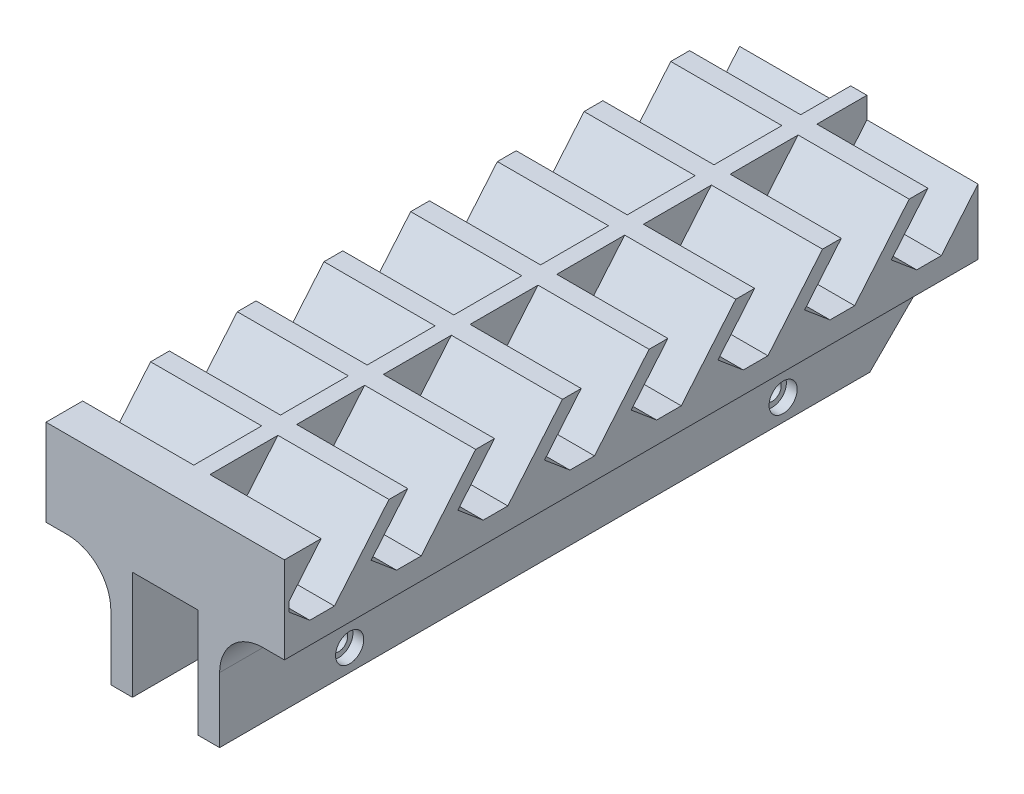
SolidWorks part; units mm, degrees
ref_plane "Front Plane" through (0, 0, 0) normal (0, 0, 1) x (1, 0, 0)
ref_plane "Top Plane" through (0, 0, 0) normal (0, 1, 0) x (1, 0, 0)
ref_plane "Right Plane" through (0, 0, 0) normal (1, 0, 0) x (0, 0, -1)
sketch "Sketch1" plane through (0, 0, 0) normal (0, 0, 1) x (1, 0, 0)
  line L0 (-15.9385, 22.225) -> (15.9385, 22.225)
  line L1 (-9.5885, 15.875) -> (9.5885, 15.875)
  line L2 (-9.5885, 15.875) -> (-9.5885, -15.875)
  line L4 (9.5885, 15.875) -> (9.5885, -15.875)
  line L5 (-9.5885, 15.875) -> (9.5885, -15.875) construction
  line L6 (-9.5885, -15.875) -> (9.5885, 15.875) construction
  line L10 (-15.9385, -22.225) -> (15.9385, -22.225) construction
  line L11 (-9.5885, -15.875) -> (9.5885, -15.875) construction
  line L12 (-15.9385, 22.225) -> (-15.9385, -22.225) construction
  line L13 (-15.9385, 22.225) -> (-15.9385, -15.875)
  line L14 (-15.9385, -15.875) -> (-9.5885, -15.875)
  line L15 (15.9385, 22.225) -> (15.9385, -15.875)
  line L16 (15.9385, 22.225) -> (15.9385, -22.225) construction
  line L17 (15.9385, -15.875) -> (9.5885, -15.875)
  point P0 (0, 0)
  dimension "D2" = 19.177
  dimension "D3" = 31.75
  dimension "D1" = 6.35
extrude "Boss-Extrude1" add sketch "Sketch1" along normal mid plane 203.2
hole_wizard "#10 Clearance Hole1" positions "Sketch2" profile "Sketch3" hole size "#10" standard "ANSI Inch" end condition through all
sketch "Sketch2" plane through (15.9385, 0, 0) normal (1, 0, 0) x (0, 0, -1)
  line L0 (-101.6, -15.875) -> (101.6, -15.875) construction
  line L1 (-63.5, -9.525) -> (63.5, -9.525)
  point P0 (-63.5, -9.525)
  point P9 (63.5, -9.525)
  point P16 (0, -9.525)
  dimension "D1" = 6.35
  dimension "D2" = 127
sketch "Sketch3" plane through (15.9385, -9.525, 63.5) normal (0, 1, 0) x (0, 0, -1)
  line L0 (0, 0) -> (0, 31.877)
  line L1 (0, 31.877) -> (2.6035, 31.877)
  line L2 (2.6035, 31.877) -> (2.6035, 0)
  line L5 (2.6035, 0) -> (0, 0)
  line L11 (0, -6.35) -> (0, 107.95) construction
  dimension "Thru Hole Dia." = 5.207
  dimension "Thru Hole Depth" = 31.877
chamfer "Chamfer1" [suppressed] distance 12.7 angle 45
sketch "Sketch8" plane through (0, 22.225, 0) normal (0, 1, 0) x (1, 0, 0)
  line L0 (15.9385, -101.6) -> (-15.9385, -101.6) construction
  line L1 (-34.925, 101.6) -> (34.925, 101.6)
  line L2 (-34.925, 101.6) -> (-34.925, -101.6)
  line L3 (-34.925, -101.6) -> (34.925, -101.6)
  line L4 (34.925, 101.6) -> (34.925, -101.6)
  line L5 (-34.925, 101.6) -> (34.925, -101.6) construction
  line L6 (-34.925, -101.6) -> (34.925, 101.6) construction
  point P0 (0, 0)
  dimension "D1" = 69.85
extrude "Boss-Extrude4" add sketch "Sketch8" against normal up to surface (6.35 mm away) up to face at (0, 15.875, 0)
sketch "Sketch4" [suppressed] plane through (15.9385, 0, 0) normal (1, 0, 0) x (0, 0, -1)
  line L5 (-63.5, -3.175) -> (-63.5, 15.875) construction
  line L6 (0, 47.625) -> (-63.5, 47.625)
  line L8 (0, 47.625) -> (0, -3.175)
  line L9 (0, -3.175) -> (-63.5, -3.175)
  line L10 (-63.5, 47.625) -> (-63.5, -3.175)
  line L11 (0, 47.625) -> (-63.5, -3.175) construction
  line L12 (0, -3.175) -> (-63.5, 47.625) construction
  line L13 (-63.5, 22.225) -> (63.5, 22.225) construction
  point P0 (-31.75, 22.225)
extrude "Boss-Extrude2" [suppressed] add sketch "Sketch4" against normal blind 4.7625
sketch "Sketch5" [suppressed] plane through (-15.9385, 0, 0) normal (-1, 0, 0) x (0, 0, 1)
  line L0 (-63.5, 15.875) -> (-63.5, -3.175) construction
  line L1 (0, 47.625) -> (-63.5, 47.625)
  line L2 (0, 47.625) -> (0, 22.225)
  line L3 (0, 22.225) -> (-63.5, 22.225)
  line L4 (-63.5, 47.625) -> (-63.5, 22.225)
  line L5 (0, 47.625) -> (-63.5, 22.225) construction
  line L6 (0, 22.225) -> (-63.5, 47.625) construction
  line L7 (0, 47.625) -> (63.5, 47.625) construction
  line L8 (63.5, 22.225) -> (-63.5, 22.225) construction
  point P0 (-31.75, 34.925)
extrude "Boss-Extrude3" [suppressed] add sketch "Sketch5" against normal blind 4.7625
fillet "Fillet1" [suppressed] radius 12.7
hole_wizard "#12 Clearance Hole1" [suppressed] positions "Sketch6" profile "Sketch7" hole size "#12" standard "ANSI Inch"
sketch "Sketch6" [suppressed] plane through (-14.351, 0, 0) normal (-1, 0, 0) x (0, 0, 1)
  arc A0 (-12.7, 44.45) -> (0, 31.75) centre (-12.7, 31.75) ccw construction
  arc A1 (25.4, 31.75) -> (12.7, 44.45) centre (12.7, 31.75) ccw construction
  point P0 (-12.7, 31.75)
  point P2 (12.7, 31.75)
sketch "Sketch7" plane through (-14.351, 31.75, -12.7) normal (0, 1, 0) x (0, 0, 1)
  line L0 (0, 0) -> (0, 46.101)
  line L1 (0, 46.101) -> (2.8956, 46.101)
  line L2 (2.8956, 46.101) -> (2.8956, 0)
  line L5 (2.8956, 0) -> (0, 0)
  line L11 (0, -6.35) -> (0, 107.95) construction
  dimension "Thru Hole Dia." = 5.7912
  dimension "Thru Hole Depth" = 46.101
sketch "Sketch9" plane through (0, 0, 0) normal (1, 0, 0) x (0, 0, -1)
  line L0 (-101.6, 15.875) -> (-101.6, 22.225) construction
  line L1 (-101.6, 41.275) -> (101.6, 41.275)
  line L2 (-101.6, 41.275) -> (-101.6, 22.225)
  line L3 (-101.6, 22.225) -> (101.6, 22.225)
  line L4 (101.6, 41.275) -> (101.6, 22.225)
  line L5 (-101.6, 41.275) -> (101.6, 22.225) construction
  line L6 (-101.6, 22.225) -> (101.6, 41.275) construction
  point P0 (0, 31.75)
  dimension "D1" = 19.05
extrude "Boss-Extrude5" add sketch "Sketch9" against normal mid plane 4.7625
fillet "Fillet2" [suppressed] radius 12.7
sketch "Sketch13" plane through (15.9385, 0, 0) normal (1, 0, 0) x (0, 0, -1)
  circle A0 centre (-63.5, -9.525) radius 4.1275
  circle A1 centre (63.5, -9.525) radius 4.1275
  circle A3 centre (63.5, -9.525) radius 2.6035 construction
  dimension "D1" = 8.255
extrude "Cut-Extrude1" cut sketch "Sketch13" against normal blind 3.175
fillet "Fillet3" radius 12.7 2 edges at (15.9385, 15.875, 0) (-15.9385, 15.875, 0)
fillet "Fillet4" [suppressed] radius 12.7
sketch "Sketch14" plane through (2.3813, 0, 0) normal (1, 0, 0) x (0, 0, -1)
  line L0 (-101.6, 31.75) -> (101.6, 31.75) construction
  line L1 (-101.6, 41.275) -> (-101.6, 22.225) construction
  line L2 (101.6, 22.225) -> (101.6, 41.275) construction
  point P6 (-88.9, 31.75)
  point P9 (-63.5, 31.75)
  point P10 (-38.1, 31.75)
  point P11 (-12.7, 31.75)
  point P12 (12.7, 31.75)
  point P13 (38.1, 31.75)
  point P14 (63.5, 31.75)
  point P15 (88.9, 31.75)
  point P17 (0, 0)
  dimension "D2" = 12.7
  dimension "D3" = 12.7
  dimension "D1" = 8
hole_wizard "1/4 (0.25) Diameter Hole1" positions "Sketch14" profile "Sketch15" hole size "1/4" standard "ANSI Inch"
sketch "Sketch15" plane through (2.3813, 31.75, -88.9) normal (0, 1, 0) x (0, 0, -1)
  line L0 (0, 0) -> (0, 13.8457)
  line L1 (0, 13.8457) -> (3.175, 11.938)
  line L2 (3.175, 11.938) -> (3.175, 0)
  line L5 (3.175, 0) -> (0, 0)
  line L10 (0, 13.8457) -> (-3.175, 11.938) construction
  line L11 (0, -6.35) -> (0, 107.95) construction
  dimension "Hole Dia." = 6.35
  dimension "Hole Depth" = 11.938
  dimension "Drill Angle" = 118
sketch "Sketch16" plane through (0, 0, 0) normal (1, 0, 0) x (0, 0, -1)
  line L0 (-86.9452, 22.225) -> (-70.9604, 41.275)
  line L1 (-94.7373, 36.648) -> (-83.0627, 26.852) construction
  line L2 (-101.6, 28.4693) -> (-90.8548, 41.275)
  line L3 (-101.6, 28.4693) -> (-94.1583, 22.225)
  line L4 (101.6, 22.225) -> (101.6, 41.275)
  line L5 (101.6, 41.275) -> (-101.6, 41.275)
  line L6 (-101.6, 41.275) -> (-101.6, 22.225)
  line L7 (-101.6, 22.225) -> (101.6, 22.225)
  line L8 (101.6, 22.225) -> (101.6, 41.275)
  line L9 (101.6, 41.275) -> (-101.6, 41.275)
  line L10 (-101.6, 41.275) -> (-101.6, 22.225)
  line L11 (-101.6, 22.225) -> (101.6, 22.225)
  line L12 (-81.4396, 22.225) -> (-65.4548, 41.275)
  line L13 (-57.6627, 26.852) -> (-69.3373, 36.648) construction
  line L14 (-56.0396, 22.225) -> (-40.0548, 41.275)
  line L15 (-61.5452, 22.225) -> (-45.5604, 41.275)
  line L16 (-30.6396, 22.225) -> (-14.6548, 41.275)
  line L17 (-36.1452, 22.225) -> (-20.1604, 41.275)
  line L18 (-5.2396, 22.225) -> (10.7452, 41.275)
  line L19 (-10.7452, 22.225) -> (5.2396, 41.275)
  line L20 (20.1604, 22.225) -> (36.1452, 41.275)
  line L21 (14.6548, 22.225) -> (30.6396, 41.275)
  line L22 (45.5604, 22.225) -> (61.5452, 41.275)
  line L23 (40.0548, 22.225) -> (56.0396, 41.275)
  line L24 (70.9604, 22.225) -> (86.9452, 41.275)
  line L25 (65.4548, 22.225) -> (81.4396, 41.275)
  line L26 (96.3604, 22.225) -> (101.6, 28.4693)
  line L27 (90.8548, 22.225) -> (101.6, 35.0307)
  line L28 (-76.2, 28.4693) -> (-68.7583, 22.225)
  line L29 (-50.8, 28.4693) -> (-43.3583, 22.225)
  line L30 (-25.4, 28.4693) -> (-17.9583, 22.225)
  line L31 (0, 28.4693) -> (7.4417, 22.225)
  line L32 (25.4, 28.4693) -> (32.8417, 22.225)
  line L33 (50.8, 28.4693) -> (58.2417, 22.225)
  line L34 (76.2, 28.4693) -> (83.6417, 22.225)
  line L35 (-100.33, 27.4037) -> (-100.33, 29.9829)
  point P4 (-88.9, 31.75)
  point P6 (-63.5, 31.75)
  point P7 (-38.1, 31.75)
  point P11 (-12.7, 31.75)
  point P12 (12.7, 31.75)
  point P13 (38.1, 31.75)
  point P14 (63.5, 31.75)
  point P15 (88.9, 31.75)
  point P20 (-88.9, 31.75)
  point P29 (-63.5, 31.75)
  dimension "D3" = 40
  dimension "D4" = 15.24
  dimension "D7" = 1.27
  dimension "D1" = 0
  dimension "D2" = 8
  dimension "D5" = 8
  dimension "D6" = 8
extrude "Boss-Extrude13" add sketch "Sketch16" along normal up to surface and the other way up to surface contours L9 L10 L2 | L3 L35 L2 | L10 L11 L3 | L11 L12 L9 L0 | L28 L12 L11 | L15 L11 L14 L9 | L29 L14 L11 | L17 L11 L16 L9 | L30 L16 L11 | L19 L11 L18 L9 | L31 L18 L11 | L21 L11 L20 L9 | L32 L20 L11 | L23 L11 L22 L9 | L33 L22 L11 | L25 L11 L24 L9 | L34 L24 L11 | L27 L11 L26 L8 | L26 L11 L8 up to face at (34.925, 19.05, 0) other way up to face at (-34.925, 19.05, 0)
chamfer "Chamfer2" distance 12.7 angle 45 2 edges at (-12.7635, -15.875, -101.6) (12.7635, -15.875, -101.6)
